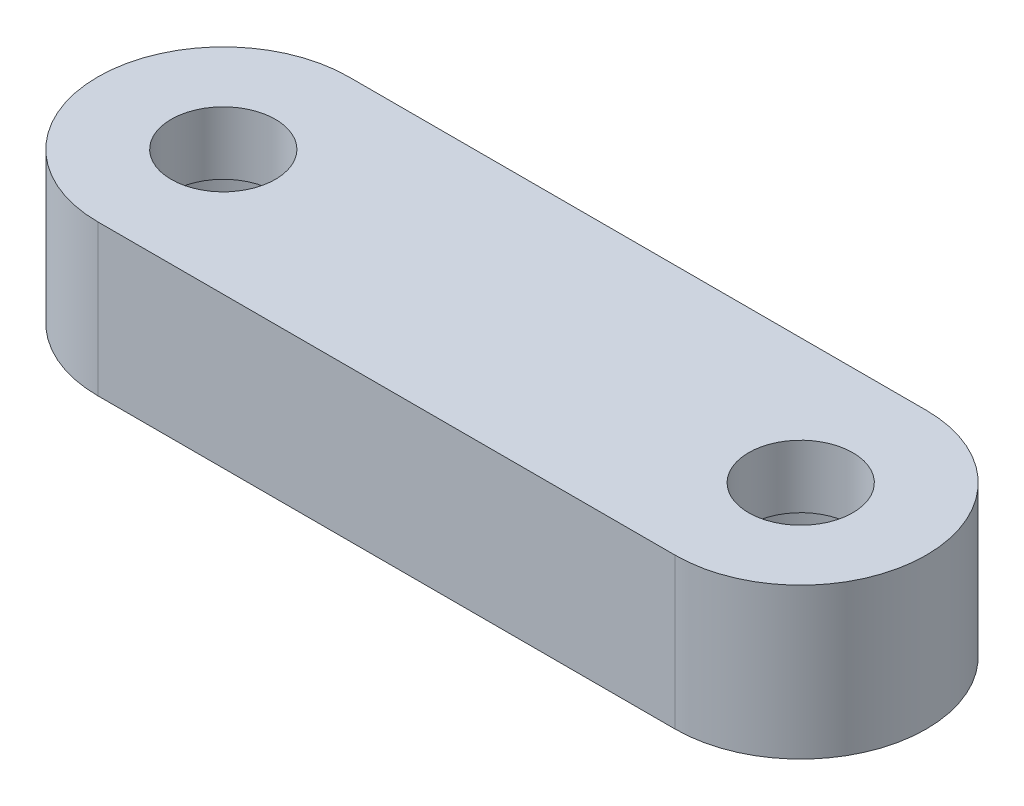
SolidWorks part; units mm, degrees
ref_plane "前视基准面" through (0, 0, 0) normal (0, 0, 1) x (1, 0, 0)
ref_plane "上视基准面" through (0, 0, 0) normal (0, 1, 0) x (1, 0, 0)
ref_plane "右视基准面" through (0, 0, 0) normal (1, 0, 0) x (0, 0, -1)
sketch "草图1" plane through (0, 0, 0) normal (0, 1, 0) x (1, 0, 0)
  line L0 (0, 0) -> (23, 0) construction
  line L1 (0, 5) -> (23, 5)
  line L4 (0, -5) -> (23, -5)
  arc A2 (0, 5) -> (0, -5) centre (0, 0) ccw
  arc A3 (23, -5) -> (23, 5) centre (23, 0) ccw
  point P3 (11.5, 0)
  dimension "D1" = 10
  dimension "D2" = 23
extrude "凸台-拉伸1" add sketch "草图1" along normal blind 6
sketch "草图2" plane through (0, 0, 0) normal (0, 0, 1) x (1, 0, 0)
  line L0 (0, 6) -> (0, 0) construction
  line L1 (0, 0) -> (-3.75, 0)
  line L2 (-5, 0) -> (0, 0) construction
  line L3 (-3.75, 0) -> (-3.75, 3.5)
  line L4 (-3.75, 3.5) -> (-2.075, 3.5)
  line L5 (-2.075, 3.5) -> (-2.075, 6)
  line L6 (0, 6) -> (-5, 6) construction
  line L7 (-2.075, 6) -> (0, 6)
  line L8 (0, 6) -> (0, 0)
  dimension "D1" = 4.15
  dimension "D2" = 7.5
  dimension "D3" = 3.5
revolve "切除-旋转1" cut sketch "草图2" angle 360 about L0
sketch "草图3" plane through (0, 0, 0) normal (0, 0, 1) x (1, 0, 0)
  line L0 (23, 0) -> (23, 6) construction
  line L1 (23, 0) -> (19.25, 0)
  line L2 (0, 0) -> (23, 0) construction
  line L3 (19.25, 0) -> (19.25, 3.5)
  line L4 (19.25, 3.5) -> (20.925, 3.5)
  line L5 (20.925, 3.5) -> (20.925, 6)
  line L6 (0, 6) -> (23, 6) construction
  line L7 (20.925, 6) -> (23, 6)
  line L8 (23, 0) -> (23, 6)
  dimension "D1" = 4.15
  dimension "D2" = 7.5
  dimension "D3" = 3.5
revolve "切除-旋转2" cut sketch "草图3" angle 360 about L0
